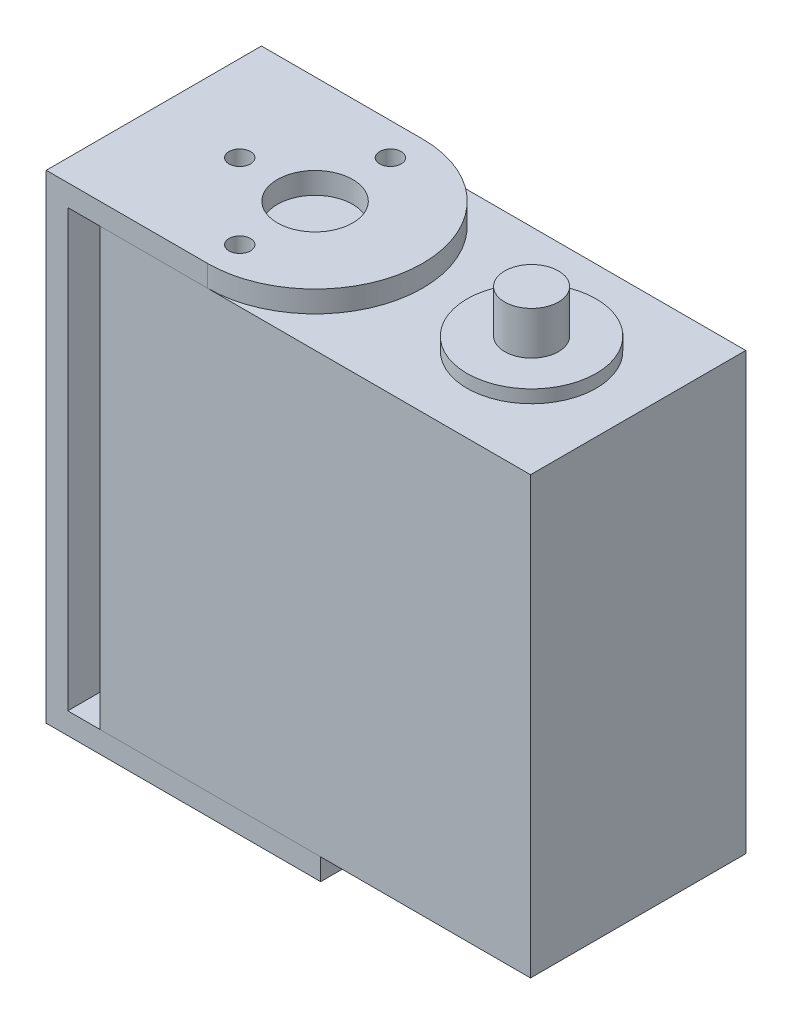
SolidWorks part; units mm, degrees
ref_plane "前视基准面" through (0, 0, 0) normal (0, 0, 1) x (1, 0, 0)
ref_plane "上视基准面" through (0, 0, 0) normal (0, 1, 0) x (1, 0, 0)
ref_plane "右视基准面" through (0, 0, 0) normal (1, 0, 0) x (0, 0, -1)
sketch "草图1" plane through (0, 0, 0) normal (0, 0, 1) x (1, 0, 0)
  line L1 (0, 0) -> (40, 0)
  line L2 (0, 0) -> (0, 40.5)
  line L3 (0, 40.5) -> (40, 40.5)
  line L4 (40, 0) -> (40, 40.5)
  dimension "D1" = 40.5
  dimension "D2" = 40
extrude "凸台-拉伸1" add sketch "草图1" along normal blind 20
sketch "草图2" plane through (0, 40.5, 0) normal (0, 1, 0) x (1, 0, 0)
  line L0 (20, 0) -> (20, -20) construction
  line L1 (40, 0) -> (0, 0) construction
  line L2 (40, -20) -> (0, -20) construction
  line L3 (0, -10) -> (40, -10) construction
  line L4 (0, -20) -> (0, 0) construction
  line L5 (40, -20) -> (40, 0) construction
  circle A0 centre (30.1, -10) radius 6
  point P14 (20, -10)
  dimension "D1" = 10.1
extrude "凸台-拉伸2" add sketch "草图2" along normal blind 2
ref_plane "基准面1" through (0, 20.25, 0) normal (0, 1, 0) x (1, 0, 0)
mirror "镜向1" about plane through (0, 20.25, 0) normal (0, 1, 0) of "凸台-拉伸2"
sketch "草图4" plane through (0, 42.5, 0) normal (0, 1, 0) x (1, 0, 0)
  circle A0 centre (30.1, -10) radius 2.5
extrude "凸台-拉伸3" add sketch "草图4" along normal blind 2.5
sketch "草图5" plane through (0, -2, 0) normal (0, -1, 0) x (1, 0, 0)
  circle A0 centre (30.1, 10) radius 2.5
extrude "凸台-拉伸4" add sketch "草图5" along normal blind 2.5
sketch "草图6" plane through (0, 40.5, 0) normal (0, 1, 0) x (1, 0, 0)
  line L0 (0, -20) -> (0, 0) construction
  line L1 (40, 0) -> (0, 0) construction
  circle A0 centre (9.98, -3) radius 1
  circle A1 centre (9.98, -17) radius 1
  circle A2 centre (2.98, -10) radius 1
  dimension "D1" = 9.98
  dimension "D4" = 7
  dimension "D2" = 3
  dimension "D5" = 7
  dimension "D3" = 2
extrude "切除-拉伸1" cut sketch "草图6" against normal blind 2.5
sketch "草图7" plane through (0, 0, 0) normal (0, -1, 0) x (1, 0, 0)
  line L0 (0, 20) -> (0, 0) construction
  line L1 (0, 20) -> (40, 20) construction
  circle A0 centre (2.5, 17.5) radius 1
  circle A1 centre (17.5, 17.5) radius 1
  circle A2 centre (17.5, 2.5) radius 1
  circle A3 centre (2.5, 2.5) radius 1
  dimension "D1" = 2.5
  dimension "D2" = 2.5
  dimension "D3" = 2
  dimension "D4" = 2
extrude "切除-拉伸2" cut sketch "草图7" against normal blind 2.5
sketch "草图8" plane through (0, -2, 0) normal (0, -1, 0) x (1, 0, 0)
  circle A0 centre (30.1, 10) radius 2.5 construction
  circle A1 centre (30.1, 10) radius 6
  circle A2 centre (30.1, 10) radius 6
  circle A3 centre (30.1, 10) radius 2.5
  dimension "D1" = 0
extrude "切除-拉伸3" cut sketch "草图8" against normal blind 0.5
sketch "草图9" plane through (0, -4.5, 0) normal (0, -1, 0) x (1, 0, 0)
  circle A1 centre (30.1, 10) radius 2.5
  circle A2 centre (30.1, 10) radius 2.5
  dimension "D1" = 0
extrude "凸台-拉伸5" add sketch "草图9" along normal blind 1
sketch "草图10" plane through (0, 42.5, 0) normal (0, 1, 0) x (1, 0, 0)
  circle A0 centre (30.1, -10) radius 2.5 construction
  circle A1 centre (30.1, -10) radius 6
  circle A2 centre (30.1, -10) radius 6
  circle A3 centre (30.1, -10) radius 2.5
  dimension "D1" = 0
extrude "切除-拉伸4" cut sketch "草图10" against normal blind 0.8
sketch "草图11" plane through (0, 45, 0) normal (0, 1, 0) x (1, 0, 0)
  circle A1 centre (30.1, -10) radius 2.5
  circle A2 centre (30.1, -10) radius 2.5
  dimension "D1" = 0
extrude "凸台-拉伸6" add sketch "草图11" along normal blind 0.7
sketch "草图13" plane through (0, 0, 0) normal (0, -1, 0) x (1, 0, 0)
  line L0 (3.5, 17.5) -> (3.5, 2.5) construction
  line L1 (3.5, 2.5) -> (16.5, 2.5) construction
  line L2 (16.5, 2.5) -> (16.5, 17.5) construction
  line L3 (16.5, 17.5) -> (3.5, 17.5) construction
  line L4 (3.5, 17.5) -> (16.5, 2.5) construction
  line L5 (3.5, 2.5) -> (16.5, 17.5) construction
  line L6 (10, 10) -> (12.2214, 10) construction
  circle A0 centre (2.5, 17.5) radius 1 construction
  circle A1 centre (2.5, 17.5) radius 1 construction
  circle A2 centre (2.5, 2.5) radius 1 construction
  circle A3 centre (17.5, 2.5) radius 1 construction
  circle A4 centre (17.5, 17.5) radius 1 construction
  circle A5 centre (10, 10) radius 0.5
  dimension "D1" = 1
extrude "切除-拉伸5" cut sketch "草图13" against normal blind 1
sketch "草图14" plane through (0, -5.5, 0) normal (0, -1, 0) x (1, 0, 0)
  circle A2 centre (30.1, 10) radius 3
  circle A3 centre (30.1, 10) radius 3
  dimension "D1" = 0.5
extrude "凸台-拉伸7" add sketch "草图14" against normal up to surface (4 mm away) up to face at (30.1, -1.5, 7.5)
sketch "草图15" plane through (0, 0, 0) normal (0, -1, 0) x (1, 0, 0)
  line L0 (0, 20) -> (40, 20) construction
  line L1 (-3.5, 0) -> (23.5, 0)
  line L2 (-3.5, 0) -> (-3.5, 20)
  line L3 (-3.5, 20) -> (23.5, 20)
  line L4 (23.5, 0) -> (23.5, 20)
  line L5 (-3.5, 0) -> (23.5, 20) construction
  line L6 (-3.5, 20) -> (23.5, 0) construction
  circle A0 centre (2.5, 2.5) radius 1 construction
  circle A1 centre (17.5, 2.5) radius 1 construction
  circle A2 centre (17.5, 17.5) radius 1 construction
  circle A3 centre (2.5, 17.5) radius 1 construction
  circle A4 centre (2.5, 2.5) radius 1
  circle A5 centre (17.5, 2.5) radius 1
  circle A6 centre (17.5, 17.5) radius 1
  circle A7 centre (2.5, 17.5) radius 1
  circle A9 centre (10, 10) radius 3.5
  point P0 (10, 10)
  dimension "D2" = 7
  dimension "D1" = 27
extrude "凸台-拉伸8" add sketch "草图15" along normal blind 2 separate body
sketch "草图16" plane through (0, 40.5, 0) normal (0, 1, 0) x (1, 0, 0)
  line L0 (9.98, -3) -> (9.98, -17) construction
  line L1 (-3.5, 0) -> (-3.5, -20)
  line L2 (-3.5, -20) -> (9.98, -20)
  line L3 (-3.5, 0) -> (9.98, 0)
  circle A0 centre (9.98, -10) radius 3.5
  arc A1 (9.98, -20) -> (9.98, 0) centre (9.98, -10) ccw
  circle A2 centre (9.98, -17) radius 1 construction
  circle A3 centre (9.98, -3) radius 1 construction
  circle A4 centre (2.98, -10) radius 1 construction
  circle A5 centre (9.98, -17) radius 1
  circle A6 centre (9.98, -3) radius 1
  circle A7 centre (2.98, -10) radius 1
  dimension "D1" = 7
extrude "凸台-拉伸9" add sketch "草图16" along normal blind 2 separate body
sketch "草图18" plane through (23.5, 0, 0) normal (1, 0, 0) x (0, 0, -1)
  line L4 (0, 0) -> (-20, 0)
  line L5 (-20, 0) -> (-20, -2)
  line L6 (-20, -2) -> (0, -2)
  line L7 (0, -2) -> (0, 0)
  line L8 (0, 0) -> (-20, 0)
  line L9 (-20, 0) -> (-20, -2)
  line L10 (-20, -2) -> (0, -2)
  line L11 (0, -2) -> (0, 0)
  dimension "D1" = 0
extrude "切除-拉伸6" cut sketch "草图18" against normal blind 3
sketch "草图19" plane through (-3.5, 0, 0) normal (-1, 0, 0) x (0, 0, 1)
  line L4 (20, 0) -> (0, 0)
  line L5 (0, 0) -> (0, -2)
  line L6 (0, -2) -> (20, -2)
  line L7 (20, -2) -> (20, 0)
  line L8 (20, 0) -> (0, 0)
  line L9 (0, 0) -> (0, -2)
  line L10 (0, -2) -> (20, -2)
  line L11 (20, -2) -> (20, 0)
  dimension "D1" = 0
extrude "凸台-拉伸10" add sketch "草图19" along normal blind 1.5
sketch "草图20" plane through (-3.5, 0, 0) normal (-1, 0, 0) x (0, 0, 1)
  line L4 (0, 40.5) -> (20, 40.5)
  line L5 (20, 40.5) -> (20, 42.5)
  line L6 (20, 42.5) -> (0, 42.5)
  line L7 (0, 42.5) -> (0, 40.5)
  line L8 (0, 40.5) -> (20, 40.5)
  line L9 (20, 40.5) -> (20, 42.5)
  line L10 (20, 42.5) -> (0, 42.5)
  line L11 (0, 42.5) -> (0, 40.5)
  dimension "D1" = 0
extrude "凸台-拉伸11" add sketch "草图20" along normal up to surface (1.5 mm away) up to face at (-5, -1, 10)
sketch "草图21" plane through (0, 0, 0) normal (0, 1, 0) x (1, 0, 0)
  line L0 (20.5, -20) -> (-5, -20) construction
  line L1 (-5, 0) -> (-3, 0)
  line L2 (-5, 0) -> (-5, -20)
  line L3 (-5, -20) -> (-3, -20)
  line L4 (-3, 0) -> (-3, -20)
  dimension "D1" = 2
extrude "凸台-拉伸12" add sketch "草图21" along normal up to surface (40.5 mm away) up to face at (4.99, 40.5, 10)
sketch "草图22" plane through (-5, 0, 0) normal (-1, 0, 0) x (0, 0, 1)
  line L0 (10, 42.5) -> (10, -2) construction
  line L1 (20, 42.5) -> (0, 42.5) construction
  line L2 (0, -2) -> (20, -2) construction
  line L5 (6.35, 7) -> (13.65, 7)
  line L6 (6.35, 7) -> (6.35, 33.5)
  line L7 (6.35, 33.5) -> (13.65, 33.5)
  line L8 (13.65, 7) -> (13.65, 33.5)
  line L9 (6.35, 7) -> (13.65, 33.5) construction
  line L10 (6.35, 33.5) -> (13.65, 7) construction
  circle A0 centre (6.35, 33.5) radius 1.25
  circle A1 centre (13.65, 33.5) radius 1.25
  circle A2 centre (6.35, 7) radius 1.25
  circle A3 centre (13.65, 7) radius 1.25
  point P6 (10, 20.25)
  point P9 (10, 30.734)
  dimension "D1" = 2.5
  dimension "D4" = 2.5
  dimension "D5" = 2.5
  dimension "D6" = 2.5
  dimension "D2" = 26.5
  dimension "D3" = 7.3
extrude "切除-拉伸7" cut sketch "草图22" against normal up to surface (2 mm away) contours L6 A0 L7 | L7 A0 L6 | L7 A1 L8 | L8 A1 L7 | L5 A3 L8 | L8 A3 L5 | L6 A2 L5 | L5 A2 L6 up to face at (-3, 20.25, 10)
sketch "草图23" plane through (-5, 0, 0) normal (-1, 0, 0) x (0, 0, 1)
  line L0 (10, 42.5) -> (10, -2) construction
  line L1 (20, 42.5) -> (0, 42.5) construction
  line L2 (0, -2) -> (20, -2) construction
  circle A0 centre (10, 20.25) radius 2.5
  dimension "D1" = 5
extrude "切除-拉伸8" cut sketch "草图23" against normal blind 2
